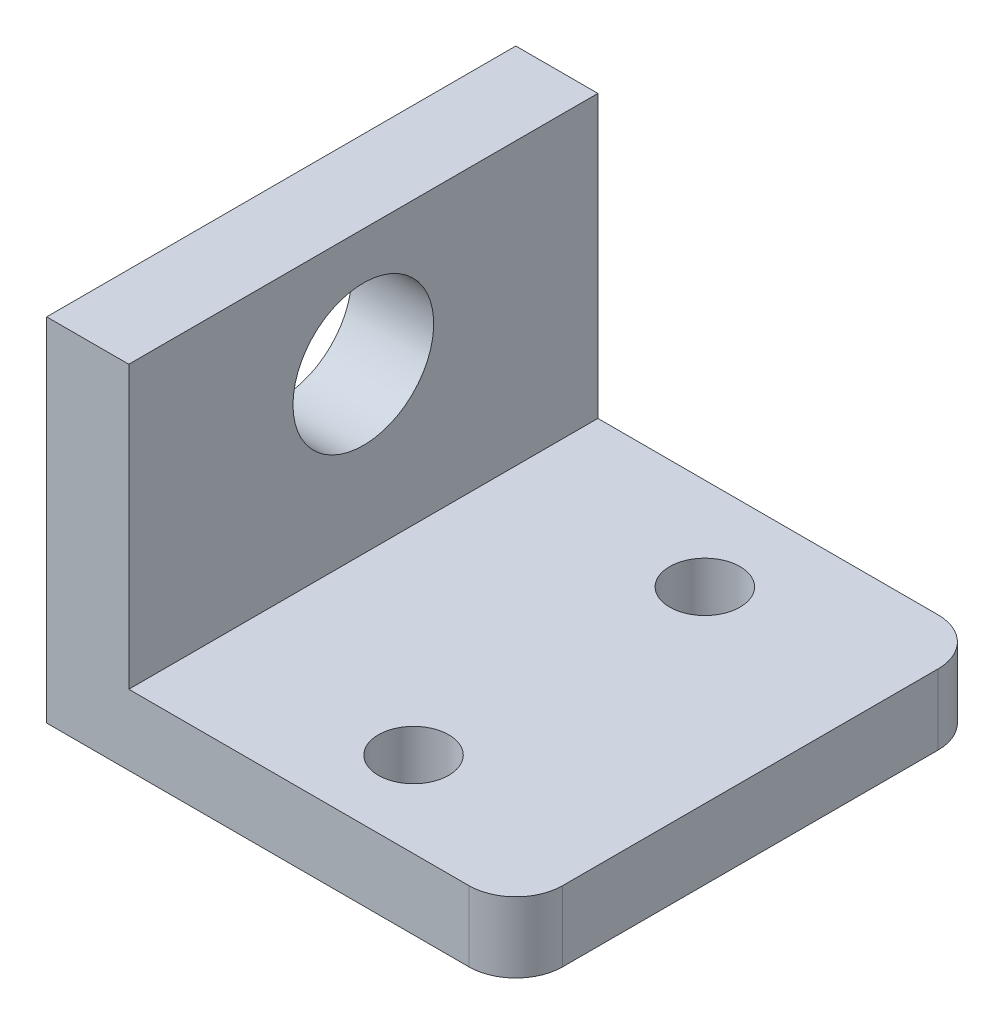
SolidWorks part; units mm, degrees
ref_plane "Front Plane" through (0, 0, 0) normal (0, 0, 1) x (1, 0, 0)
ref_plane "Top Plane" through (0, 0, 0) normal (0, 1, 0) x (1, 0, 0)
ref_plane "Right Plane" through (0, 0, 0) normal (1, 0, 0) x (0, 0, -1)
sketch "Sketch1" plane through (0, 0, 0) normal (0, 1, 0) x (1, 0, 0)
  line L1 (10, -10) -> (-10, -10)
  line L2 (10, -10) -> (10, 10)
  line L3 (10, 10) -> (-10, 10)
  line L4 (-10, -10) -> (-10, 10)
  line L5 (10, -10) -> (-10, 10) construction
  line L6 (10, 10) -> (-10, -10) construction
  point P0 (0, 0)
  dimension "D1" = 20
  dimension "D2" = 20
extrude "Boss-Extrude1" add sketch "Sketch1" along normal blind 3
sketch "Sketch2" plane through (0, 3, 0) normal (0, 1, 0) x (1, 0, 0)
  line L0 (10, 10) -> (-10, 10) construction
  line L1 (-10, -10) -> (-6.5, -10)
  line L2 (-10, -10) -> (-10, 10)
  line L3 (-10, 10) -> (-6.5, 10)
  line L4 (-6.5, -10) -> (-6.5, 10)
  point P5 (0, 0)
  dimension "D1" = 3.5
extrude "Boss-Extrude2" add sketch "Sketch2" along normal blind 12
sketch "Sketch3" plane through (-10, 0, 0) normal (-1, 0, 0) x (0, 0, 1)
  line L0 (-10, 15) -> (10, 15) construction
  circle A0 centre (0, 10) radius 3
  dimension "D1" = 6
  dimension "D2" = 5
extrude "Cut-Extrude1" cut sketch "Sketch3" against normal blind 12
fillet "Fillet1" radius 2 2 edges at (10, 1.5, 10) (10, 1.5, -10)
sketch "Sketch4" plane through (0, 3, 0) normal (0, 1, 0) x (1, 0, 0)
  line L0 (10, -8) -> (10, 8) construction
  circle A0 centre (2, 6.0602) radius 1.5
  circle A1 centre (2, -6.3598) radius 1.5
  point P4 (0, 0)
  dimension "D1" = 3
  dimension "D2" = 8
extrude "Cut-Extrude2" cut sketch "Sketch4" against normal blind 12
